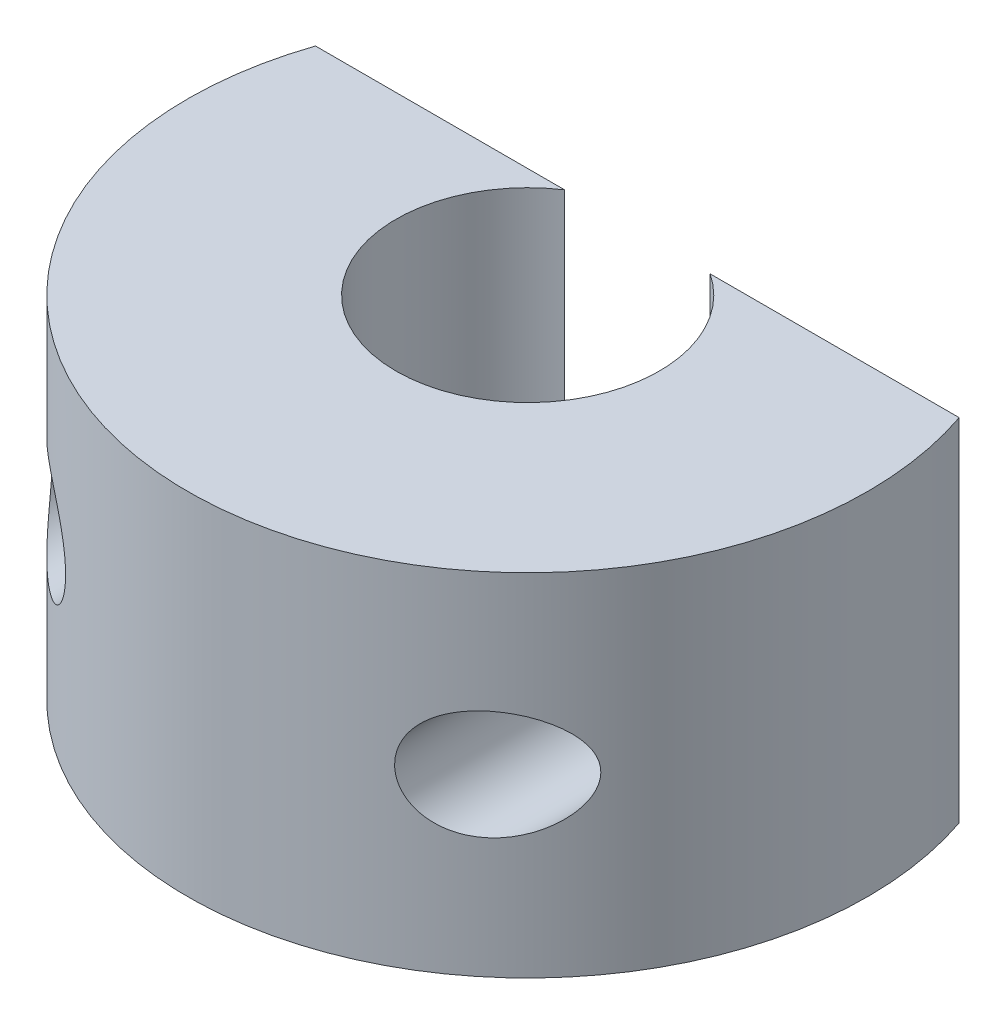
SolidWorks part; units mm, degrees
material "3.0205 (EN-AW 1200)"
ref_plane "Plan de face" through (0, 0, 0) normal (0, 0, 1) x (1, 0, 0)
ref_plane "Plan de dessus" through (0, 0, 0) normal (0, 1, 0) x (1, 0, 0)
ref_plane "Plan de droite" through (0, 0, 0) normal (1, 0, 0) x (0, 0, -1)
sketch "Esquisse1" plane through (0, 0, 0) normal (0, 1, 0) x (1, 0, 0)
  line L3 (-7.3357, 2.5) -> (-1.6583, 2.5)
  line L4 (1.6583, 2.5) -> (7.3357, 2.5)
  arc A0 (-7.3357, 2.5) -> (7.3357, 2.5) centre (0, 0) ccw
  arc A1 (1.6583, 2.5) -> (-1.6583, 2.5) centre (0, 0) cw
  dimension "D3" = 15.5
  dimension "D1" = 3
  dimension "D2" = 2.5
extrude "Boss.-Extru.1" add sketch "Esquisse1" along normal mid plane 8
sketch "Esquisse2" plane through (0, 0, -2.5) normal (0, 0, -1) x (-1, 0, 0)
  line L0 (-5, 0) -> (5, 0) construction
  circle A0 centre (-5, 0) radius 1.25
  circle A1 centre (5, 0) radius 1.25
  dimension "D1" = 2.5
  dimension "D2" = 10
extrude "Enlèv. mat.-Extru.1" cut sketch "Esquisse2" against normal through all
